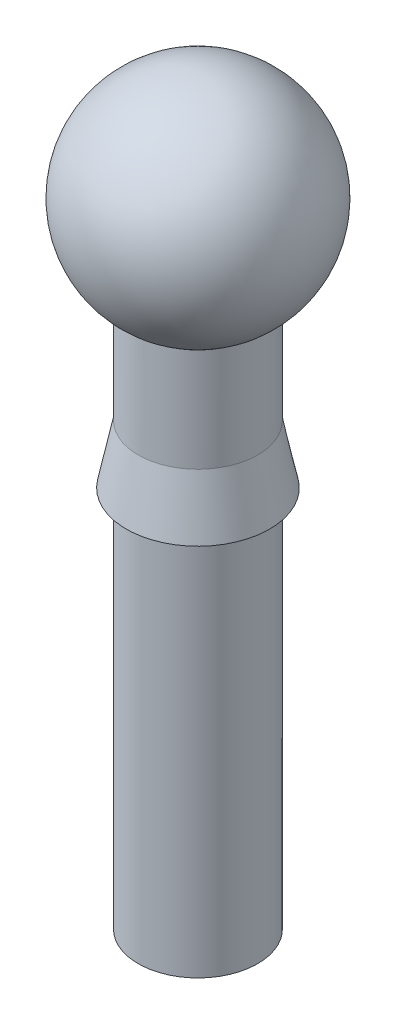
SolidWorks part; units mm, degrees
ref_plane "前视基准面" through (0, 0, 0) normal (0, 0, 1) x (1, 0, 0)
ref_plane "上视基准面" through (0, 0, 0) normal (0, 1, 0) x (1, 0, 0)
ref_plane "右视基准面" through (0, 0, 0) normal (1, 0, 0) x (0, 0, -1)
other "Configuration Table"
sketch "草图1" plane through (0, 0, 0) normal (0, 0, 1) x (1, 0, 0)
  line L0 (0, 0) -> (0, 34.268) construction
  line L1 (2.5, 22.7583) -> (2.5, 18.4348)
  line L2 (2.5, 18.4348) -> (3, 16)
  line L3 (3, 16) -> (2.5, 16)
  line L4 (2.5, 16) -> (2.5, 0)
  line L5 (2.5, 0) -> (0, 0)
  line L6 (0, 0) -> (0, 31) construction
  line L7 (0, 0) -> (0, 31)
  arc A0 (2.5, 22.7583) -> (0, 31) centre (0, 26.5) ccw
  point P4 (0, 0)
  point P7 (2.5, 13.8648)
  point P12 (2.5258, 17.0284)
  point P13 (2.5, 18.4348)
  point P14 (0, 34.268)
  dimension "D1" = 9
  dimension "D4" = 10.5
  dimension "D5" = 26.5
  dimension "D2" = 2.5
  dimension "D3" = 3
  dimension "D6" = 2.5
revolve "旋转3" add sketch "草图1" angle 360 about L6
